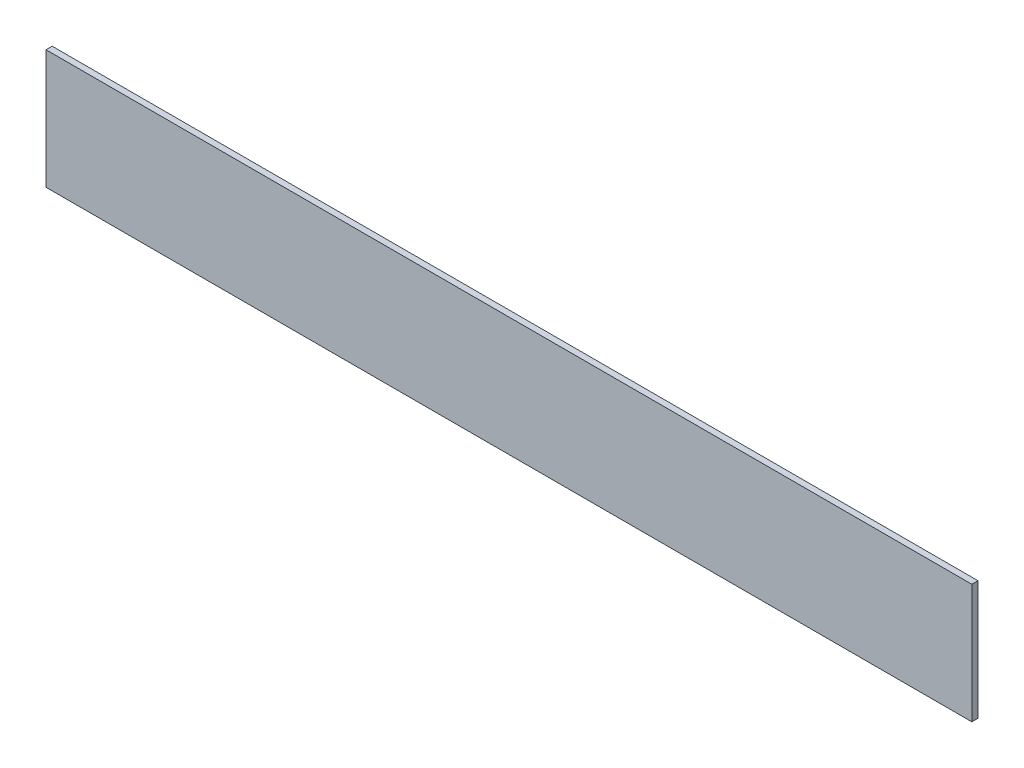
SolidWorks part; units mm, degrees
ref_plane "Front Plane" through (0, 0, 0) normal (0, 0, 1) x (1, 0, 0)
ref_plane "Top Plane" through (0, 0, 0) normal (0, 1, 0) x (1, 0, 0)
ref_plane "Right Plane" through (0, 0, 0) normal (1, 0, 0) x (0, 0, -1)
sketch "Sketch1" plane through (0, 0, 0) normal (0, 0, 1) x (1, 0, 0)
  line L0 (0, -9.65) -> (0, 9.65)
  line L1 (55, 0) -> (-55, 0) construction
  line L2 (0, 9.65) -> (-150, 9.65)
  line L4 (0, 9.65) -> (-150, 9.65)
  line L5 (0, 9.65) -> (0, -9.65)
  line L6 (0, -9.65) -> (-150, -9.65)
  line L7 (-150, 9.65) -> (-150, -9.65)
  point P6 (0, 0)
extrude "Boss-Extrude1" add sketch "Sketch1" along normal blind 1 contours L2 L7 L6 L0
